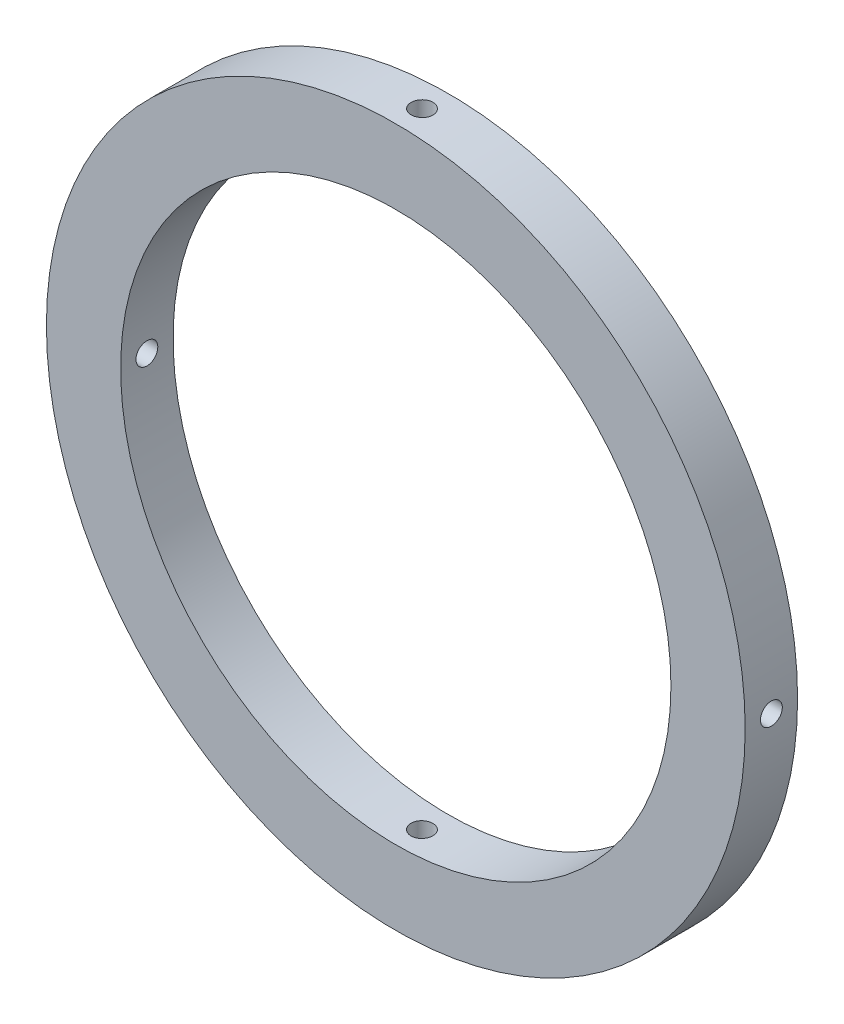
SolidWorks part; units mm, degrees
ref_plane "Front Plane" through (0, 0, 0) normal (0, 0, 1) x (1, 0, 0)
ref_plane "Top Plane" through (0, 0, 0) normal (0, 1, 0) x (1, 0, 0)
ref_plane "Right Plane" through (0, 0, 0) normal (1, 0, 0) x (0, 0, -1)
sketch "Sketch1" plane through (0, 0, 0) normal (0, 0, 1) x (1, 0, 0)
  circle A0 centre (0, 0) radius 31.5
  circle A1 centre (0, 0) radius 40
  dimension "D1" = 80
  dimension "D2" = 63
extrude "Boss-Extrude1" add sketch "Sketch1" along normal blind 6
ref_plane "Plane1" through (0, 40, 0) normal (0, 1, 0) x (1, 0, 0)
sketch "Sketch2" plane through (0, 40, 0) normal (0, 1, 0) x (1, 0, 0)
  line L1 (0, 0) -> (0, -6) construction
  circle A0 centre (0, -3) radius 1.25
  dimension "D1" = 2.5
extrude "Cut-Extrude1" cut sketch "Sketch2" against normal up to next
pattern_circular "CirPattern1" count 4 over 360 about axis through (0, 0, 6) along (0, 0, -1) of "Cut-Extrude1"
